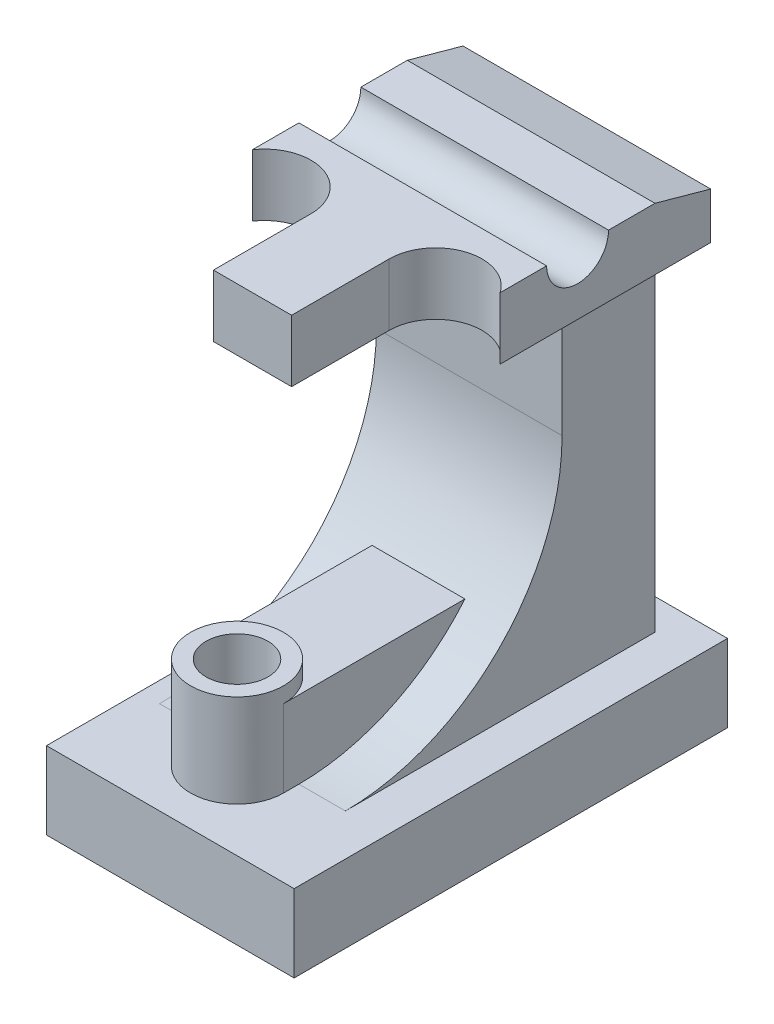
SolidWorks part; units mm, degrees
ref_plane "Front Plane" through (0, 0, 0) normal (0, 0, 1) x (1, 0, 0)
ref_plane "Top Plane" through (0, 0, 0) normal (0, 1, 0) x (1, 0, 0)
ref_plane "Right Plane" through (0, 0, 0) normal (1, 0, 0) x (0, 0, -1)
sketch "Sketch1" plane through (0, 0, 0) normal (0, 1, 0) x (1, 0, 0)
  line L1 (-36.5539, 41.9702) -> (43.4461, 41.9702)
  line L2 (-36.5539, 41.9702) -> (-36.5539, -98.0298)
  line L3 (-36.5539, -98.0298) -> (43.4461, -98.0298)
  line L4 (43.4461, 41.9702) -> (43.4461, -98.0298)
  dimension "D1" = 80
  dimension "D2" = 140
extrude "Boss-Extrude1" add sketch "Sketch1" along normal blind 25
sketch "Sketch2" plane through (0, 0, 0) normal (1, 0, 0) x (0, 0, -1)
  line L0 (31.9702, 25) -> (31.9702, 135)
  line L1 (-98.0298, 25) -> (41.9702, 25) construction
  line L2 (31.9702, 135) -> (1.9702, 135)
  line L3 (1.9702, 135) -> (1.9702, 95)
  line L4 (41.9702, 25) -> (41.9702, 0) construction
  line L5 (-68.0298, 25) -> (31.9702, 25)
  arc A0 (1.9702, 95) -> (-68.0298, 25) centre (-68.0298, 95) cw
  dimension "D3" = 70
  dimension "D1" = 110
  dimension "D2" = 30
  dimension "D4" = 10
extrude "Boss-Extrude2" add sketch "Sketch2" along normal blind 30 and the other way blind 30
ref_plane "Plane1" through (0, 55, 0) normal (0, 1, 0) x (1, 0, 0)
sketch "Sketch3" plane through (0, 55, 0) normal (0, 1, 0) x (1, 0, 0)
  line L0 (-36.5539, -98.0298) -> (43.4461, -98.0298) construction
  circle A0 centre (0, -73.0298) radius 10
  circle A1 centre (0, -73.0298) radius 15
  point P5 (0, 0)
  dimension "D1" = 20
  dimension "D2" = 30
  dimension "D3" = 25
extrude "Boss-Extrude3" add sketch "Sketch3" against normal up to next
ref_plane "Plane3" through (0, 50, 0) normal (0, 1, 0) x (1, 0, 0)
sketch "Sketch4" plane through (0, 50, 0) normal (0, 1, 0) x (1, 0, 0)
  line L0 (14.9557, -74.1814) -> (15, -74.1814)
  line L1 (-15, -7.5473) -> (15, -7.5473) construction
  line L2 (-15, -7.5473) -> (-15, -74.1814)
  line L3 (-15, -74.1814) -> (-14.9557, -74.1814)
  line L4 (15, -7.5473) -> (15, -74.1814)
  circle A0 centre (0, -73.0298) radius 15 construction
  arc A1 (14.9557, -74.1814) -> (-14.9557, -74.1814) centre (0, -73.0298) ccw
  point P6 (0, 0)
extrude "Boss-Extrude7" add sketch "Sketch4" against normal blind 30 contours L1 L2 A1 L4
sketch "Sketch7" plane through (0, 135, 0) normal (0, 1, 0) x (1, 0, 0)
  line L0 (12.629, -36.5127) -> (12.629, -68.0298)
  line L1 (-12.629, -68.0298) -> (12.629, -68.0298)
  line L2 (-40, -28.0298) -> (-40, 39.9702)
  line L3 (-40, 39.9702) -> (40, 39.9702)
  line L4 (40, -28.0298) -> (40, 39.9702)
  line L5 (-13.3201, -32.012) -> (40, 39.9702) construction
  line L6 (-40, 39.9702) -> (40, -68.0298) construction
  line L7 (0, -14.0298) -> (0, -132.4908) construction
  line L8 (-30, 31.9702) -> (30, 31.9702) construction
  line L9 (-12.629, -36.5127) -> (-12.629, -68.0298)
  arc A0 (40, -28.0298) -> (12.629, -36.5127) centre (27.629, -36.5127) ccw
  arc A1 (-40, -28.0298) -> (-12.629, -36.5127) centre (-27.629, -36.5127) cw
  point P0 (0, -14.0298)
  dimension "D3" = 15
  dimension "D1" = 108
  dimension "D2" = 80
  dimension "D4" = 68
  dimension "D5" = 8
extrude "Boss-Extrude8" add sketch "Sketch7" along normal blind 20
sketch "Sketch8" plane through (40, 0, 0) normal (1, 0, 0) x (0, 0, -1)
  line L0 (-28.0298, 155) -> (39.9702, 155) construction
  line L3 (21.9702, 155) -> (39.9702, 155)
  line L5 (-13.0298, 155) -> (6.9702, 155)
  line L6 (39.9702, 155) -> (39.9702, 150)
  line L7 (39.9702, 155) -> (39.9702, 135) construction
  line L8 (21.9702, 155) -> (39.9702, 150)
  arc A0 (-13.0298, 155) -> (6.9702, 155) centre (-3.0298, 155) ccw
  dimension "D1" = 10
  dimension "D2" = 18
  dimension "D3" = 33
extrude "Cut-Extrude1" cut sketch "Sketch8" against normal up to next
